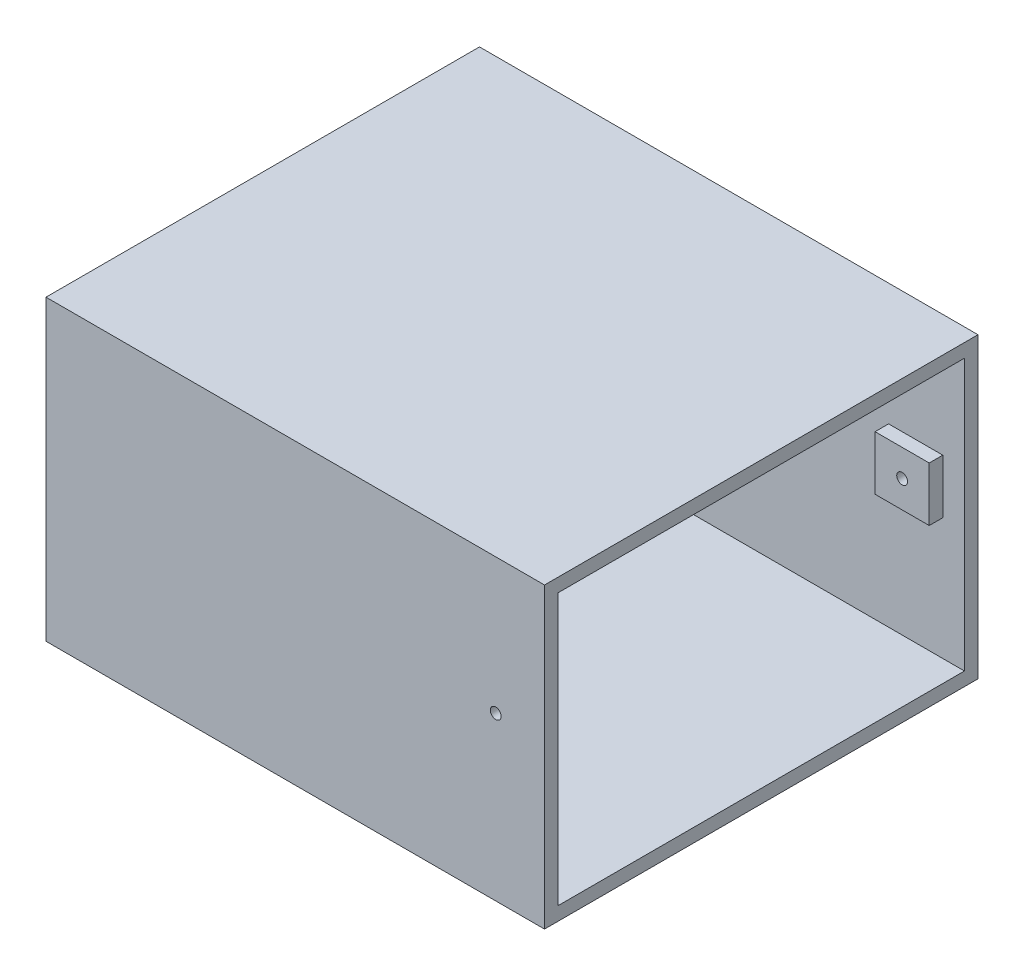
SolidWorks part; units mm, degrees
ref_plane "Plano frontal" through (0, 0, 0) normal (0, 0, 1) x (1, 0, 0)
ref_plane "Plano superior" through (0, 0, 0) normal (0, 1, 0) x (1, 0, 0)
ref_plane "Plano direito" through (0, 0, 0) normal (1, 0, 0) x (0, 0, -1)
sketch "Esboço2" plane through (0, 0, 0) normal (1, 0, 0) x (0, 0, -1)
  line L1 (-40, -27.5) -> (40, -27.5)
  line L2 (-40, -27.5) -> (-40, 27.5)
  line L3 (-40, 27.5) -> (40, 27.5)
  line L4 (40, -27.5) -> (40, 27.5)
  line L5 (-40, -27.5) -> (40, 27.5) construction
  line L6 (-40, 27.5) -> (40, -27.5) construction
  point P0 (0, 0)
  dimension "D1" = 80
  dimension "D2" = 55
extrude "Ressalto-extrusão1" add sketch "Esboço2" against normal blind 92
sketch "Esboço3" plane through (0, 0, 0) normal (1, 0, 0) x (0, 0, -1)
  line L1 (-37.5, -25) -> (37.5, -25)
  line L2 (-37.5, -25) -> (-37.5, 25)
  line L3 (-37.5, 25) -> (37.5, 25)
  line L4 (37.5, -25) -> (37.5, 25)
  line L5 (-37.5, -25) -> (37.5, 25) construction
  line L6 (-37.5, 25) -> (37.5, -25) construction
  point P0 (0, 0)
  dimension "D1" = 75
  dimension "D2" = 50
extrude "Corte-extrusão1" cut sketch "Esboço3" against normal blind 89.5
sketch "Esboço4" plane through (-92, 0, 0) normal (-1, 0, 0) x (0, 0, 1)
  line L1 (-37.5, 16.5) -> (-2.5, 16.5)
  line L2 (-37.5, 16.5) -> (-37.5, 1.5)
  line L3 (-37.5, 1.5) -> (-2.5, 1.5)
  line L4 (-2.5, 16.5) -> (-2.5, 1.5)
  line L6 (40, -27.5) -> (-40, -27.5) construction
  line L7 (-40, -27.5) -> (-40, 27.5) construction
  dimension "D1" = 29
  dimension "D2" = 15
  dimension "D3" = 35
  dimension "D4" = 2.5
extrude "Corte-extrusão2" cut sketch "Esboço4" against normal up to surface (2.5 mm away) up to face at (-89.5, 0, 0)
sketch "Esboço5" plane through (0, 0, 40) normal (0, 0, 1) x (1, 0, 0)
  line L0 (0, 27.5) -> (0, -27.5) construction
  line L2 (-92, 27.5) -> (0, 27.5) construction
  circle A0 centre (-9, 2.5) radius 1
  dimension "D1" = 2
  dimension "D3" = 25
  dimension "D2" = 9
extrude "Corte-extrusão3" cut sketch "Esboço5" against normal through all
sketch "Esboço6" plane through (0, 0, 37.5) normal (0, 0, -1) x (-1, 0, 0)
  line L1 (4, -2.5) -> (14, -2.5)
  line L2 (4, -2.5) -> (4, 7.5)
  line L3 (4, 7.5) -> (14, 7.5)
  line L4 (14, -2.5) -> (14, 7.5)
  line L5 (4, -2.5) -> (14, 7.5) construction
  line L6 (4, 7.5) -> (14, -2.5) construction
  point P0 (9, 2.5)
  dimension "D1" = 10
  dimension "D2" = 10
extrude "Ressalto-extrusão2" add sketch "Esboço6" along normal blind 2.5
sketch "Esboço8" plane through (0, 0, 35) normal (0, 0, -1) x (-1, 0, 0)
  circle A0 centre (9, 2.5) radius 1
  dimension "D1" = 2
extrude "Corte-extrusão4" cut sketch "Esboço8" against normal through all
mirror "Espelhar3" about plane through (0, 0, 0) normal (0, 0, 1) of "Ressalto-extrusão2", "Corte-extrusão4"
